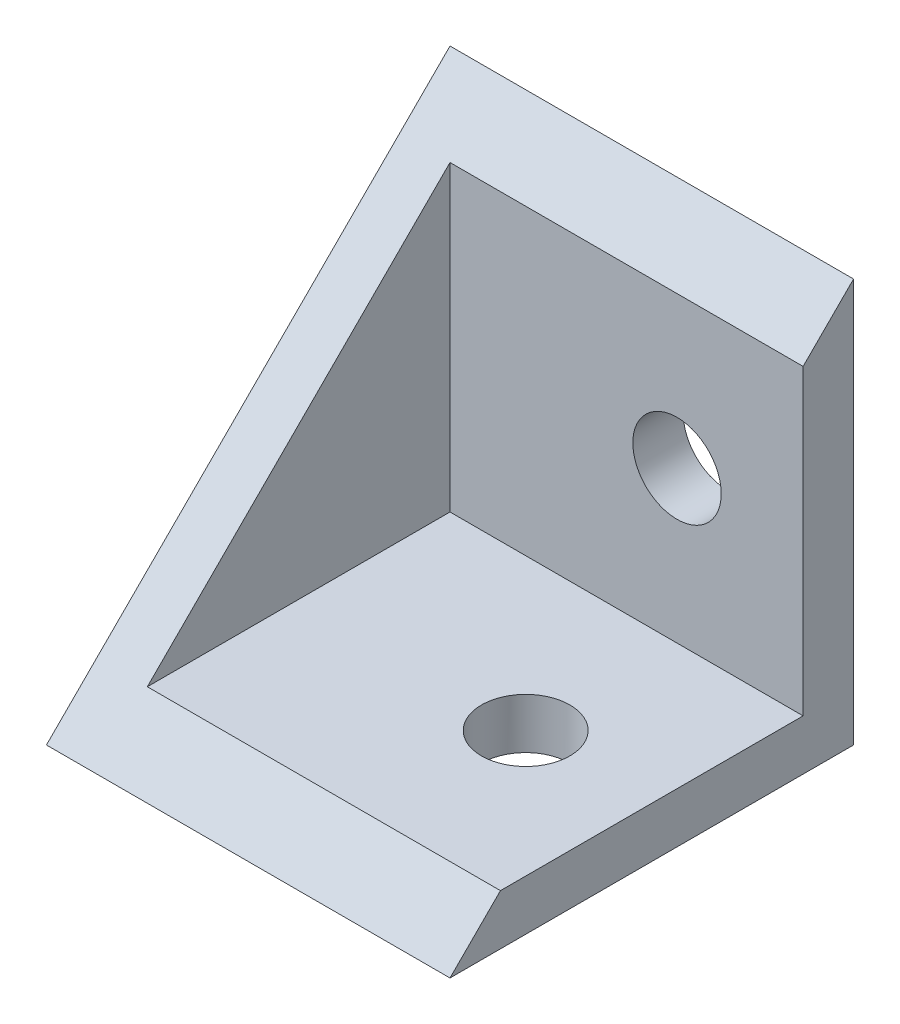
SolidWorks part; units mm, degrees
ref_plane "Front Plane" through (0, 0, 0) normal (0, 0, 1) x (1, 0, 0)
ref_plane "Top Plane" through (0, 0, 0) normal (0, 1, 0) x (1, 0, 0)
ref_plane "Right Plane" through (0, 0, 0) normal (1, 0, 0) x (0, 0, -1)
sketch "Sketch1" plane through (0, 0, 0) normal (0, 1, 0) x (1, 0, 0)
  line L1 (-12.7, -12.7) -> (12.7, -12.7)
  line L2 (-12.7, -12.7) -> (-12.7, 12.7)
  line L3 (-12.7, 12.7) -> (12.7, 12.7)
  line L4 (12.7, -12.7) -> (12.7, 12.7)
  line L5 (-12.7, -12.7) -> (12.7, 12.7) construction
  line L6 (-12.7, 12.7) -> (12.7, -12.7) construction
  point P0 (0, 0)
  dimension "D1" = 25.4
  dimension "D2" = 25.4
extrude "Boss-Extrude1" add sketch "Sketch1" along normal blind 25.4
sketch "Sketch2" plane through (12.7, 0, 0) normal (1, 0, 0) x (0, 0, -1)
  line L0 (-12.7, 25.4) -> (12.7, 25.4)
  line L1 (12.7, 25.4) -> (-12.7, 0)
  line L2 (-12.7, 0) -> (-12.7, 25.4)
extrude "Cut-Extrude1" cut sketch "Sketch2" against normal blind 25.4
sketch "Sketch3" plane through (12.7, 0, 0) normal (1, 0, 0) x (0, 0, -1)
  line L0 (-9.525, 3.175) -> (9.525, 3.175)
  line L1 (-12.7, 0) -> (12.7, 25.4) construction
  line L2 (9.525, 3.175) -> (9.525, 22.225)
  line L3 (-12.7, 0) -> (12.7, 0) construction
  line L4 (12.7, 25.4) -> (12.7, 0) construction
  dimension "D1" = 3.175
  dimension "D2" = 3.175
extrude "Cut-Extrude2" cut sketch "Sketch3" against normal blind 22.225 and the other way through all
sketch "Sketch4" plane through (0, 0, -9.525) normal (0, 0, 1) x (1, 0, 0)
  line L0 (12.7, 22.225) -> (12.7, 3.175) construction
  line L1 (-12.7, 0) -> (12.7, 0) construction
  circle A0 centre (4.7625, 12.7) radius 2.7813
  dimension "D1" = 5.5626
  dimension "D2" = 7.9375
  dimension "D3" = 12.7
extrude "Cut-Extrude3" cut sketch "Sketch4" against normal blind 22.225
sketch "Sketch5" plane through (0, 3.175, 0) normal (0, 1, 0) x (1, 0, 0)
  line L0 (12.7, 9.525) -> (12.7, -9.525) construction
  line L1 (12.7, 12.7) -> (-12.7, 12.7) construction
  circle A0 centre (4.7625, 0) radius 2.7813
  dimension "D1" = 5.5626
  dimension "D2" = 7.9375
  dimension "D3" = 12.7
extrude "Cut-Extrude4" cut sketch "Sketch5" against normal blind 22.225
